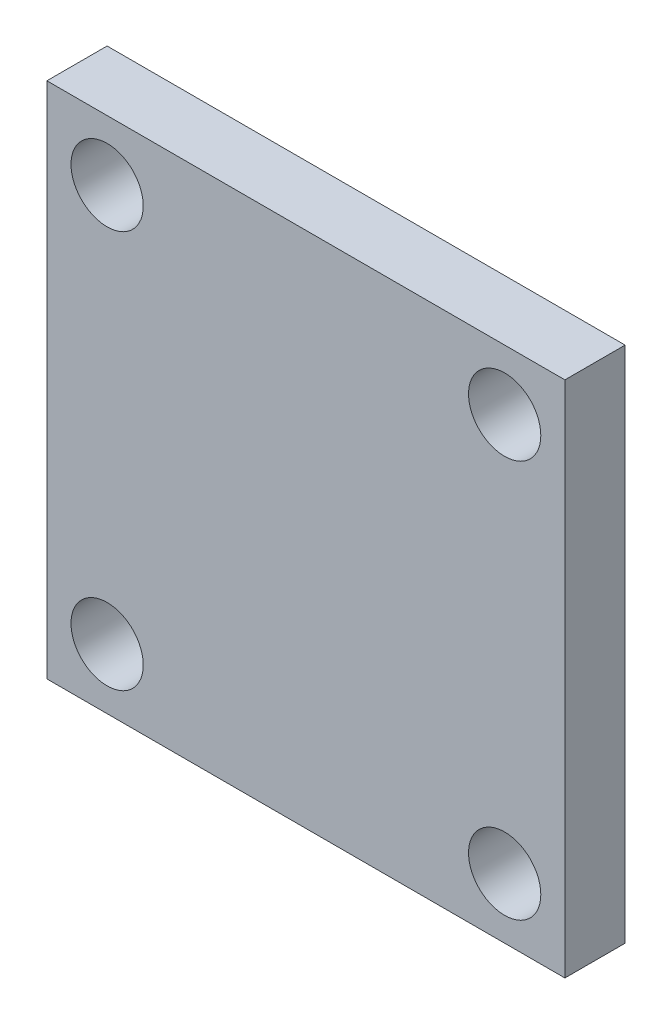
SolidWorks part; units mm, degrees
ref_plane "前视基准面" through (0, 0, 0) normal (0, 0, 1) x (1, 0, 0)
ref_plane "上视基准面" through (0, 0, 0) normal (0, 1, 0) x (1, 0, 0)
ref_plane "右视基准面" through (0, 0, 0) normal (1, 0, 0) x (0, 0, -1)
sketch "草图1" plane through (0, 0, 0) normal (0, 0, 1) x (1, 0, 0)
  line L1 (-21.5, 21.5) -> (21.5, 21.5)
  line L2 (-21.5, 21.5) -> (-21.5, -21.5)
  line L3 (-21.5, -21.5) -> (21.5, -21.5)
  line L4 (21.5, 21.5) -> (21.5, -21.5)
  line L5 (-21.5, 21.5) -> (21.5, -21.5) construction
  line L6 (-21.5, -21.5) -> (21.5, 21.5) construction
  circle A0 centre (-16.5, -16.5) radius 3
  circle A1 centre (-16.5, 16.5) radius 3
  circle A2 centre (16.5, 16.5) radius 3
  circle A3 centre (16.5, -16.5) radius 3
  point P0 (0, 0)
  point P9 (-16.5, -16.5)
  point P19 (0, 0)
  dimension "D1" = 4
extrude "凸台-拉伸1" add sketch "草图1" along normal blind 5
